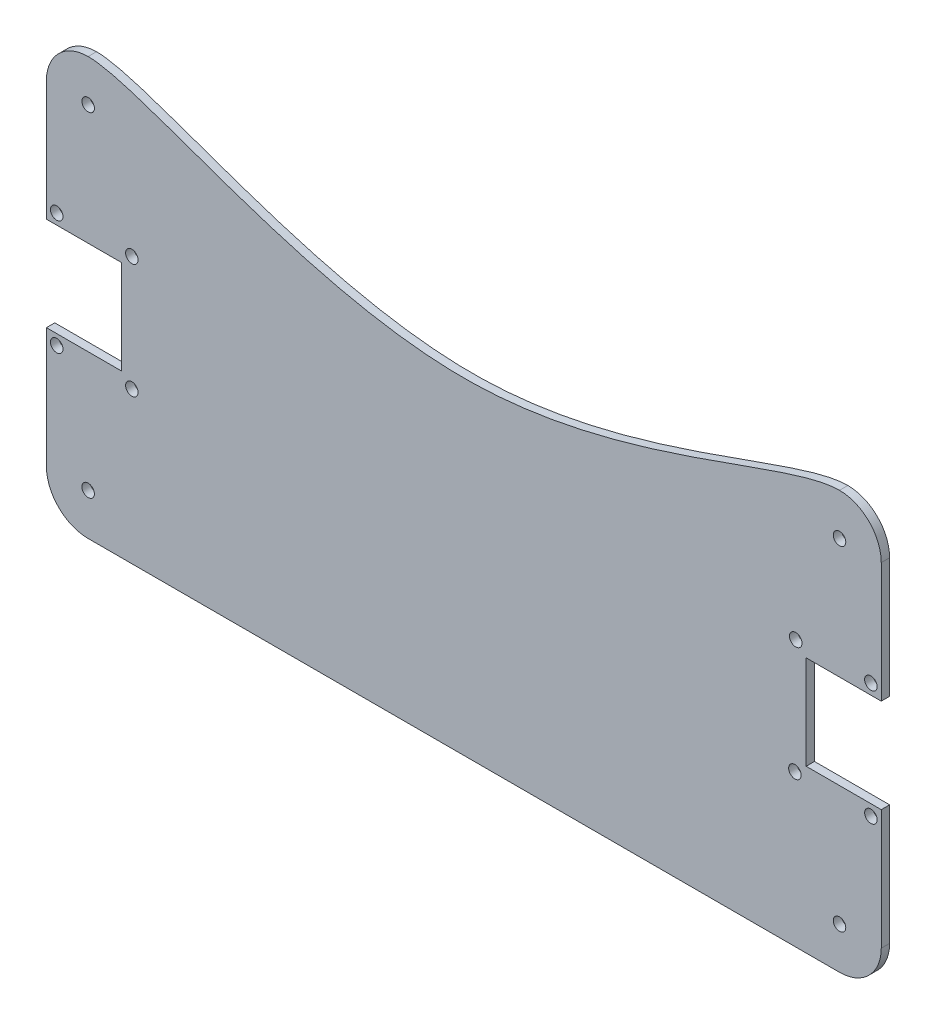
SolidWorks part; units mm, degrees
ref_plane "Front Plane" through (0, 0, 0) normal (0, 0, 1) x (1, 0, 0)
ref_plane "Top Plane" through (0, 0, 0) normal (0, 1, 0) x (1, 0, 0)
ref_plane "Right Plane" through (0, 0, 0) normal (1, 0, 0) x (0, 0, -1)
sketch "Sketch1" plane through (0, 0, 0) normal (0, 0, 1) x (1, 0, 0)
  line L0 (103.7868, 3.6154) -> (101.3064, 3.6154)
  line L2 (-96.2084, 32.3654) -> (-96.2084, 3.6154)
  line L3 (-86.2084, -57.6346) -> (93.7868, -57.6346)
  line L4 (103.7868, 32.3654) -> (103.7868, 3.6154)
  line L5 (-78.2084, -7.6346) -> (-78.2084, 3.6154)
  line L6 (-78.2084, -7.6346) -> (-78.2084, -18.8846)
  line L7 (-78.2084, 3.6154) -> (-96.2084, 3.6154)
  line L9 (-78.2084, -18.8846) -> (-96.2084, -18.8846)
  line L10 (-96.2084, -18.8846) -> (-96.2084, -47.6346)
  line L11 (85.7916, -7.6346) -> (85.7916, 3.6154)
  line L12 (85.7916, -7.6346) -> (85.7916, -18.8846)
  line L13 (85.7916, 3.6154) -> (103.7868, 3.6154)
  line L14 (85.7916, -18.8846) -> (103.7868, -18.8846)
  line L15 (103.7868, -18.8846) -> (103.7868, -47.6346)
  line L16 (-96.2084, 3.6154) -> (-93.7382, 3.6154)
  arc A0 (-96.2084, -47.6346) -> (-86.2084, -57.6346) centre (-86.2084, -47.6346) ccw
  arc A1 (93.7868, -57.6346) -> (103.7868, -47.6346) centre (93.7868, -47.6346) ccw
  arc A2 (93.7868, 42.3654) -> (103.7868, 32.3654) centre (93.7868, 32.3654) cw
  arc A3 (-86.2084, 42.3654) -> (-96.2084, 32.3654) centre (-86.2084, 32.3654) ccw
  circle A4 centre (93.7868, 32.3654) radius 1.5
  circle A5 centre (-86.2084, 32.3654) radius 1.5
  circle A6 centre (-86.2084, -47.6346) radius 1.5
  circle A7 centre (101.3064, 6.1282) radius 1.5
  circle A8 centre (83.3039, 6.1282) radius 1.5
  circle A9 centre (83.103, -21.3652) radius 1.5
  circle A10 centre (101.3064, -21.4982) radius 1.5
  circle A11 centre (-93.7382, 6.1282) radius 1.5
  circle A12 centre (-75.7379, 6.1282) radius 1.5
  circle A13 centre (-75.7379, -21.3652) radius 1.5
  circle A14 centre (-93.7382, -21.3652) radius 1.5
  circle A15 centre (93.7868, -47.6346) radius 1.5
  spline S0 degree 3 poles (93.7868, 42.3654) (80.3656, 42.377) (3.8102, -1.0441) (-72.8291, 42.3541) (-86.2084, 42.3654) knots 0 0 0 0 0.5 1 1 1 1
  dimension "D1" = 10
  dimension "D2" = 10
  dimension "D3" = 22.5
  dimension "D4" = 17.9952
extrude "Boss-Extrude5" add sketch "Sketch1" along normal blind 2 contours A2 S0 A3 L2 L7 L5 L6 L9 L10 A0 L3 A1 L15 L14 L12 L11 L13 L0 L4 A4 A5 A6 A7 A8 A9 A10 A11 A12 A13 A14
sketch "Sketch4" plane through (0, 0, 2) normal (0, 0, 1) x (1, 0, 0)
